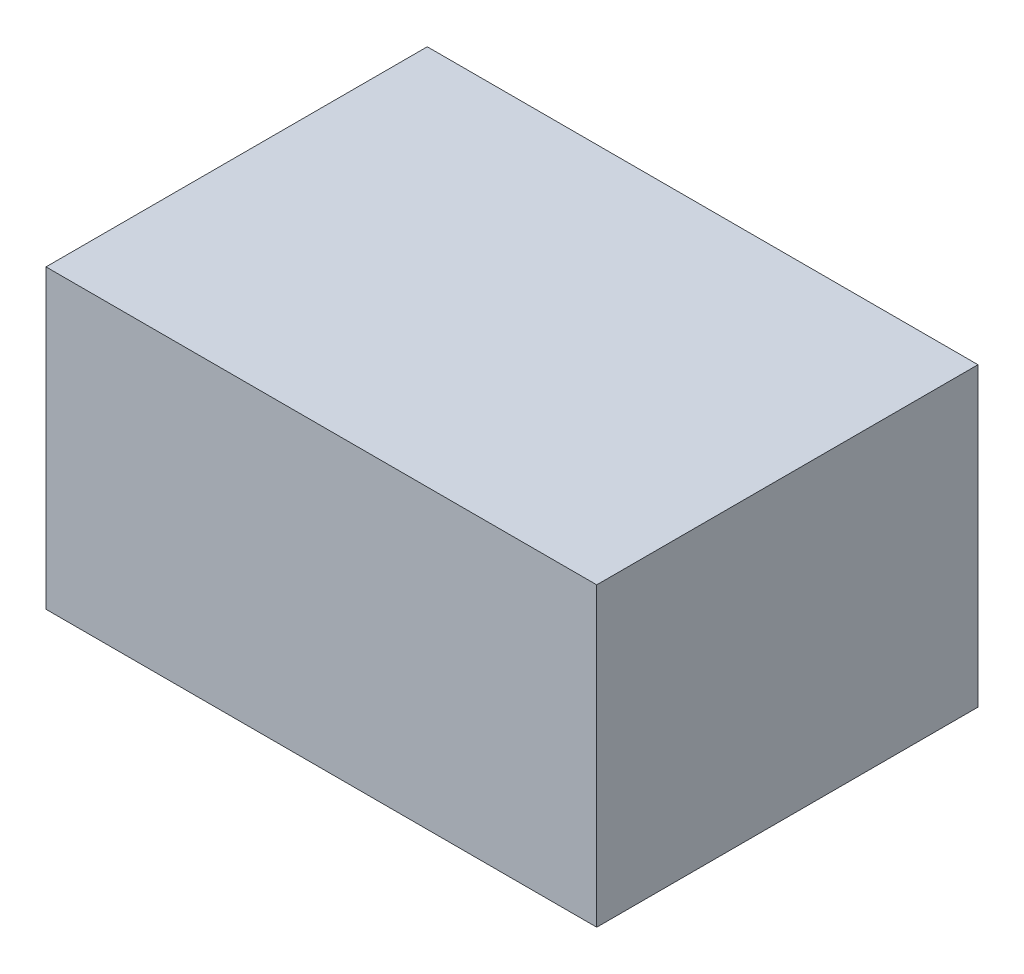
SolidWorks part; units mm, degrees
ref_plane "Front Plane" through (0, 0, 0) normal (0, 0, 1) x (1, 0, 0)
ref_plane "Top Plane" through (0, 0, 0) normal (0, 1, 0) x (1, 0, 0)
ref_plane "Right Plane" through (0, 0, 0) normal (1, 0, 0) x (0, 0, -1)
sketch "Sketch1" plane through (0, 0, 0) normal (0, 1, 0) x (1, 0, 0)
  line L1 (-10.3187, 7.1437) -> (10.3188, 7.1437)
  line L2 (-10.3187, 7.1437) -> (-10.3187, -7.1438)
  line L3 (-10.3187, -7.1438) -> (10.3188, -7.1438)
  line L4 (10.3188, 7.1437) -> (10.3188, -7.1438)
  line L5 (-10.3187, 7.1437) -> (10.3188, -7.1438) construction
  line L6 (-10.3187, -7.1438) -> (10.3188, 7.1437) construction
  point P0 (0, 0)
  dimension "D1" = 20.6375
  dimension "D2" = 14.2875
extrude "Boss-Extrude1" add sketch "Sketch1" along normal blind 11.1125
